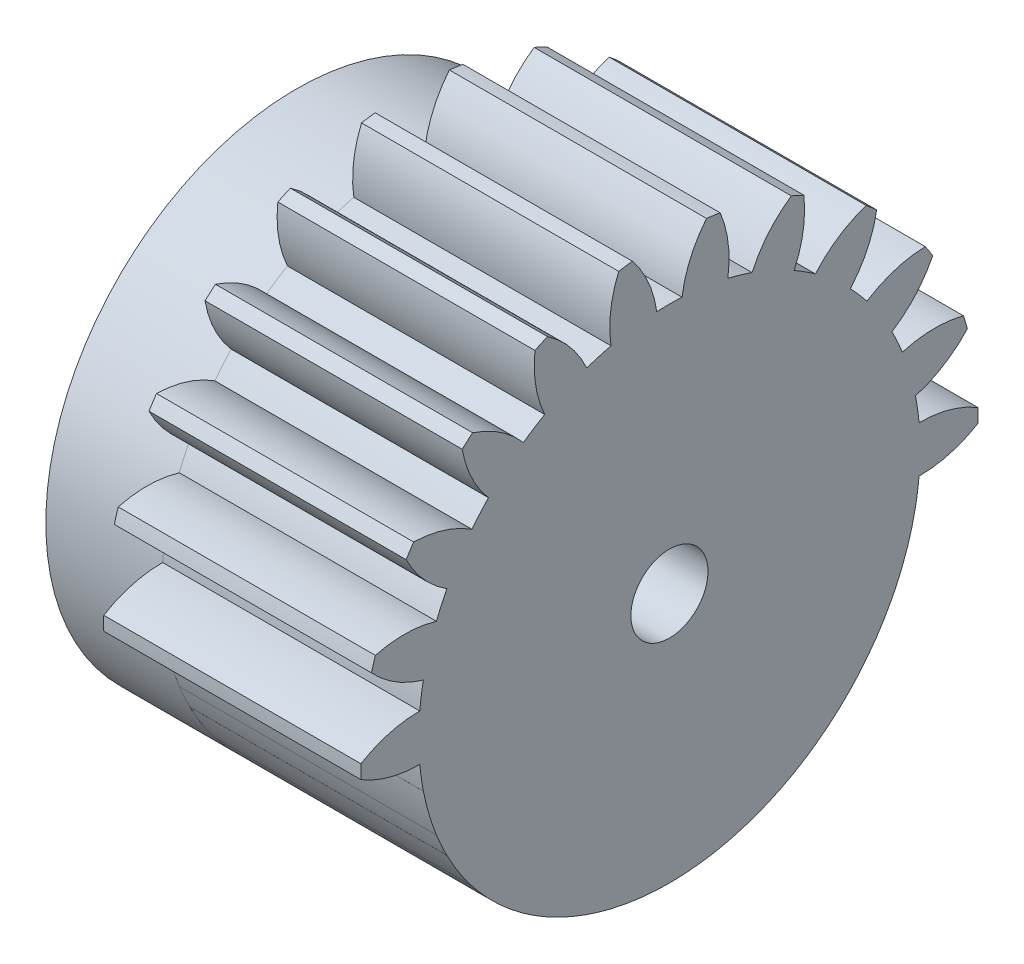
SolidWorks part; units mm, degrees
ref_plane "Front Plane" through (0, 0, 0) normal (0, 0, 1) x (1, 0, 0)
ref_plane "Top Plane" through (0, 0, 0) normal (0, 1, 0) x (1, 0, 0)
ref_plane "Right Plane" through (0, 0, 0) normal (1, 0, 0) x (0, 0, -1)
ref_plane "Plane2" through (4.0389, 0, 0) normal (1, 0, 0) x (0, 0, -1)
sketch "Sketch5" plane through (4.0389, 0, 0) normal (1, 0, 0) x (0, 0, -1)
  circle A0 centre (3.23, 4.4522) radius 1.5
  arc A1 (-8.767, 4.1839) -> (-6.4774, 3.5525) centre (-6.496, 7.9525) ccw
  arc A2 (-6.4774, 3.5525) -> (-6.3377, 2.5805) centre (3.23, 4.4522) ccw
  arc A3 (-6.3377, 2.5805) -> (-8.3567, 1.3296) centre (-5.1159, -1.6464) ccw
  arc A4 (-8.3567, 1.3296) -> (-8.2055, 0.8148) centre (3.23, 4.4522) ccw
  arc A5 (-8.2055, 0.8148) -> (-5.8308, 0.8541) centre (-7.0882, 5.0706) ccw
  arc A6 (-5.8308, 0.8541) -> (-5.4228, -0.0392) centre (3.23, 4.4522) ccw
  arc A7 (-5.4228, -0.0392) -> (-7.0076, -1.8082) centre (-3.0596, -3.7507) ccw
  arc A8 (-7.0076, -1.8082) -> (-6.7175, -2.2596) centre (3.23, 4.4522) ccw
  arc A9 (-6.7175, -2.2596) -> (-4.45, -1.5529) centre (-6.8444, 2.1386) ccw
  arc A10 (-4.45, -1.5529) -> (-3.807, -2.295) centre (3.23, 4.4522) ccw
  arc A11 (-3.807, -2.295) -> (-4.8292, -4.4389) centre (-0.4938, -5.1904) ccw
  arc A12 (-4.8292, -4.4389) -> (-4.4237, -4.7902) centre (3.23, 4.4522) ccw
  arc A13 (-4.4237, -4.7902) -> (-2.4471, -3.4733) centre (-5.7845, -0.606) ccw
  arc A14 (-2.4471, -3.4733) -> (-1.621, -4.0043) centre (3.23, 4.4522) ccw
  arc A15 (-1.621, -4.0043) -> (-1.9978, -6.3492) centre (2.3736, -5.8489) ccw
  arc A16 (-1.9978, -6.3492) -> (-1.5097, -6.5721) centre (3.23, 4.4522) ccw
  arc A17 (-1.5097, -6.5721) -> (0.0157, -4.7517) centre (-3.9943, -2.9408) ccw
  arc A18 (0.0157, -4.7517) -> (0.9579, -5.0284) centre (3.23, 4.4522) ccw
  arc A19 (0.9579, -5.0284) -> (1.257, -7.3845) centre (5.3105, -5.6729) ccw
  arc A20 (1.257, -7.3845) -> (1.7882, -7.4609) centre (3.23, 4.4522) ccw
  arc A21 (1.7882, -7.4609) -> (2.739, -5.2845) centre (-1.6189, -4.6766) ccw
  arc A22 (2.739, -5.2845) -> (3.721, -5.2845) centre (3.23, 4.4522) ccw
  arc A23 (3.721, -5.2845) -> (4.6718, -7.4609) centre (8.0788, -4.6766) ccw
  arc A24 (4.6718, -7.4609) -> (5.2029, -7.3845) centre (3.23, 4.4522) ccw
  arc A25 (5.2029, -7.3845) -> (5.502, -5.0284) centre (1.1494, -5.6729) ccw
  arc A26 (5.502, -5.0284) -> (6.4442, -4.7517) centre (3.23, 4.4522) ccw
  arc A27 (6.4442, -4.7517) -> (7.9696, -6.5721) centre (10.4542, -2.9408) ccw
  arc A28 (7.9696, -6.5721) -> (8.4577, -6.3492) centre (3.23, 4.4522) ccw
  arc A29 (8.4577, -6.3492) -> (8.0809, -4.0043) centre (4.0863, -5.8489) ccw
  arc A30 (8.0809, -4.0043) -> (8.907, -3.4733) centre (3.23, 4.4522) ccw
  arc A31 (8.907, -3.4733) -> (10.8836, -4.7902) centre (12.2444, -0.606) ccw
  arc A32 (10.8836, -4.7902) -> (11.2891, -4.4389) centre (3.23, 4.4522) ccw
  arc A33 (11.2891, -4.4389) -> (10.2669, -2.295) centre (6.9537, -5.1904) ccw
  arc A34 (10.2669, -2.295) -> (10.9099, -1.5529) centre (3.23, 4.4522) ccw
  arc A35 (10.9099, -1.5529) -> (13.1774, -2.2596) centre (13.3043, 2.1386) ccw
  arc A36 (13.1774, -2.2596) -> (13.4675, -1.8082) centre (3.23, 4.4522) ccw
  arc A37 (13.4675, -1.8082) -> (11.8827, -0.0392) centre (9.5195, -3.7507) ccw
  arc A38 (11.8827, -0.0392) -> (12.2907, 0.8541) centre (3.23, 4.4522) ccw
  arc A39 (12.2907, 0.8541) -> (14.6654, 0.8148) centre (13.5481, 5.0706) ccw
  arc A40 (14.6654, 0.8148) -> (14.8166, 1.3296) centre (3.23, 4.4522) ccw
  arc A41 (14.8166, 1.3296) -> (12.7976, 2.5805) centre (11.5758, -1.6464) ccw
  arc A42 (12.7976, 2.5805) -> (12.9374, 3.5525) centre (3.23, 4.4522) ccw
  arc A43 (12.9374, 3.5525) -> (15.227, 4.1839) centre (12.9559, 7.9525) ccw
  arc A44 (15.227, 4.1839) -> (15.227, 4.7205) centre (3.23, 4.4522) ccw
  arc A45 (15.227, 4.7205) -> (12.9374, 5.3518) centre (12.9559, 0.9519) ccw
  arc A46 (12.9374, 5.3518) -> (12.7976, 6.3238) centre (3.23, 4.4522) ccw
  arc A47 (12.7976, 6.3238) -> (14.8166, 7.5747) centre (11.5758, 10.5508) ccw
  arc A48 (14.8166, 7.5747) -> (14.6654, 8.0895) centre (3.23, 4.4522) ccw
  arc A49 (14.6654, 8.0895) -> (12.2907, 8.0503) centre (13.5481, 3.8338) ccw
  arc A50 (12.2907, 8.0503) -> (11.8827, 8.9435) centre (3.23, 4.4522) ccw
  arc A51 (11.8827, 8.9435) -> (13.4675, 10.7125) centre (9.5195, 12.655) ccw
  arc A52 (13.4675, 10.7125) -> (13.1774, 11.1639) centre (3.23, 4.4522) ccw
  arc A53 (13.1774, 11.1639) -> (10.9099, 10.4572) centre (13.3043, 6.7658) ccw
  arc A54 (10.9099, 10.4572) -> (10.2669, 11.1994) centre (3.23, 4.4522) ccw
  arc A55 (10.2669, 11.1994) -> (11.2891, 13.3432) centre (6.9537, 14.0947) ccw
  arc A56 (11.2891, 13.3432) -> (10.8836, 13.6946) centre (3.23, 4.4522) ccw
  arc A57 (10.8836, 13.6946) -> (8.907, 12.3777) centre (12.2444, 9.5103) ccw
  arc A58 (8.907, 12.3777) -> (8.0809, 12.9086) centre (3.23, 4.4522) ccw
  arc A59 (8.0809, 12.9086) -> (8.4577, 15.2536) centre (4.0863, 14.7533) ccw
  arc A60 (8.4577, 15.2536) -> (7.9696, 15.4765) centre (3.23, 4.4522) ccw
  arc A61 (7.9696, 15.4765) -> (6.4442, 13.6561) centre (10.4542, 11.8451) ccw
  arc A62 (6.4442, 13.6561) -> (5.502, 13.9327) centre (3.23, 4.4522) ccw
  arc A63 (5.502, 13.9327) -> (5.2029, 16.2889) centre (1.1494, 14.5772) ccw
  arc A64 (5.2029, 16.2889) -> (4.6718, 16.3652) centre (3.23, 4.4522) ccw
  arc A65 (4.6718, 16.3652) -> (3.721, 14.1888) centre (8.0788, 13.581) ccw
  arc A66 (3.721, 14.1888) -> (2.739, 14.1888) centre (3.23, 4.4522) ccw
  arc A67 (2.739, 14.1888) -> (1.7882, 16.3652) centre (-1.6189, 13.581) ccw
  arc A68 (1.7882, 16.3652) -> (1.257, 16.2889) centre (3.23, 4.4522) ccw
  arc A69 (1.257, 16.2889) -> (0.9579, 13.9327) centre (5.3105, 14.5772) ccw
  arc A70 (0.9579, 13.9327) -> (0.0157, 13.6561) centre (3.23, 4.4522) ccw
  arc A71 (0.0157, 13.6561) -> (-1.5097, 15.4765) centre (-3.9943, 11.8451) ccw
  arc A72 (-1.5097, 15.4765) -> (-1.9978, 15.2536) centre (3.23, 4.4522) ccw
  arc A73 (-1.9978, 15.2536) -> (-1.621, 12.9086) centre (2.3736, 14.7533) ccw
  arc A74 (-1.621, 12.9086) -> (-2.4471, 12.3777) centre (3.23, 4.4522) ccw
  arc A75 (-2.4471, 12.3777) -> (-4.4237, 13.6946) centre (-5.7845, 9.5103) ccw
  arc A76 (-4.4237, 13.6946) -> (-4.8292, 13.3432) centre (3.23, 4.4522) ccw
  arc A77 (-4.8292, 13.3432) -> (-3.807, 11.1994) centre (-0.4938, 14.0947) ccw
  arc A78 (-3.807, 11.1994) -> (-4.45, 10.4572) centre (3.23, 4.4522) ccw
  arc A79 (-4.45, 10.4572) -> (-6.7175, 11.1639) centre (-6.8444, 6.7658) ccw
  arc A80 (-6.7175, 11.1639) -> (-7.0076, 10.7125) centre (3.23, 4.4522) ccw
  arc A81 (-7.0076, 10.7125) -> (-5.4228, 8.9435) centre (-3.0596, 12.655) ccw
  arc A82 (-5.4228, 8.9435) -> (-5.8308, 8.0503) centre (3.23, 4.4522) ccw
  arc A83 (-5.8308, 8.0503) -> (-8.2055, 8.0895) centre (-7.0882, 3.8338) ccw
  arc A84 (-8.2055, 8.0895) -> (-8.3567, 7.5747) centre (3.23, 4.4522) ccw
  arc A85 (-8.3567, 7.5747) -> (-6.3377, 6.3238) centre (-5.1159, 10.5508) ccw
  arc A86 (-6.3377, 6.3238) -> (-6.4774, 5.3518) centre (3.23, 4.4522) ccw
  arc A87 (-6.4774, 5.3518) -> (-8.767, 4.7205) centre (-6.496, 0.9519) ccw
  arc A88 (-8.767, 4.7205) -> (-8.767, 4.1839) centre (3.23, 4.4522) ccw
extrude "Boss-Extrude1" add sketch "Sketch5" against normal blind 10 separate body
ref_plane "Plane3" through (0, 0, -3.23) normal (0, 0, 1) x (1, 0, 0)
sketch "Sketch10" plane through (0, 0, -3.23) normal (0, 0, 1) x (1, 0, 0)
  line L0 (-5.9611, 7.9022) -> (-5.9611, 14.2022)
  line L1 (-5.9611, 14.2022) -> (-10.4611, 14.2022)
  line L2 (-10.4611, 14.2022) -> (-10.4611, 7.9022)
  line L3 (-10.4611, 7.9022) -> (-5.9611, 7.9022)
  line L4 (-10.4611, 4.4522) -> (-5.9611, 4.4522) construction
revolve "Revolve2" add sketch "Sketch10" angle 360 about L4
sketch "Sketch11" plane through (4.0389, 0, 0) normal (1, 0, 0) x (0, 0, -1)
  line L1 (-9.2027, 3.156) -> (-6.4335, 3.156)
  line L2 (12.8934, 3.156) -> (15.6626, 3.156)
  arc A0 (-6.4335, 3.156) -> (12.8934, 3.156) centre (3.23, 4.4522) ccw
  arc A1 (-9.2027, 3.156) -> (15.6626, 3.156) centre (3.23, 4.4522) ccw
  dimension "D1" = 19.5
  dimension "D2" = 25
extrude "Cut-Extrude1" cut sketch "Sketch11" against normal blind 10
sketch "Sketch13" plane through (-10.4611, 0, 0) normal (-1, 0, 0) x (0, 0, 1)
  circle A0 centre (-3.23, 4.4522) radius 4.1
  dimension "D1" = 8.2
extrude "Cut-Extrude2" cut sketch "Sketch13" against normal up to surface (4.5 mm away) up to face at (-5.9611, 4.4522, -4.73)
sketch "Sketch14" plane through (-5.9611, 0, 0) normal (-1, 0, 0) x (0, 0, 1)
  circle A0 centre (-3.23, 4.4522) radius 3.25
  dimension "D1" = 6.5
extrude "Cut-Extrude3" cut sketch "Sketch14" against normal blind 3
